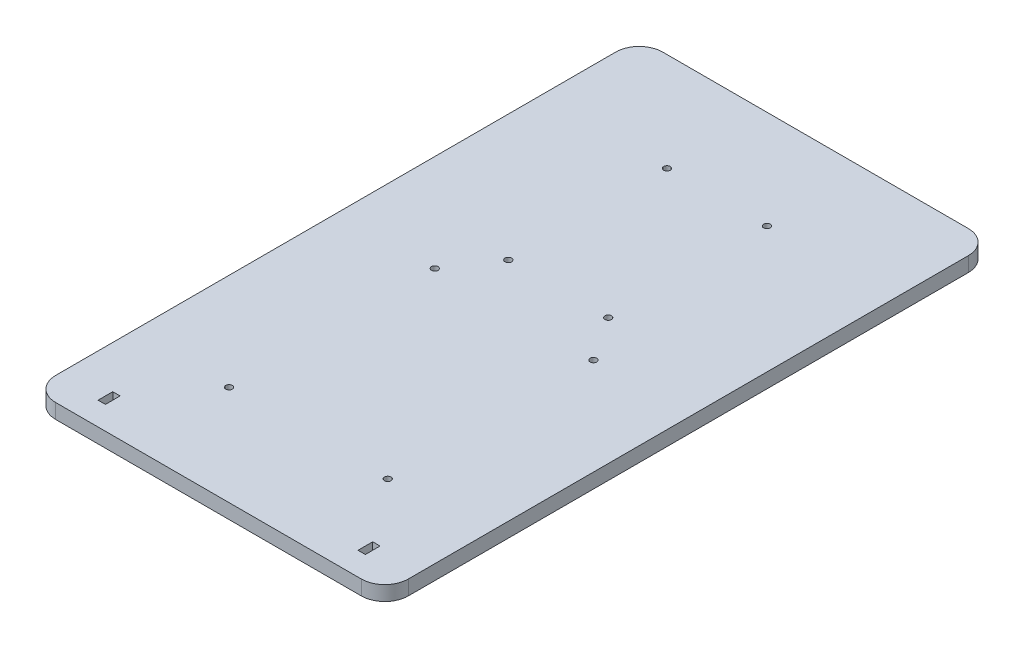
SolidWorks part; units mm, degrees
ref_plane "Front Plane" through (0, 0, 0) normal (0, 0, 1) x (1, 0, 0)
ref_plane "Top Plane" through (0, 0, 0) normal (0, 1, 0) x (1, 0, 0)
ref_plane "Right Plane" through (0, 0, 0) normal (1, 0, 0) x (0, 0, -1)
sketch "Sketch3" plane through (0, 0, 0) normal (0, 1, 0) x (1, 0, 0)
  line L4 (152.4, 0) -> (0, 0)
  line L5 (76.2, 262.3393) -> (76.2, 0) construction
  line L6 (18.4411, 16.3877) -> (21.6161, 16.3877)
  line L7 (18.4411, 16.3877) -> (18.4411, 10.0377)
  line L8 (18.4411, 10.0377) -> (21.6161, 10.0377)
  line L9 (21.6161, 16.3877) -> (21.6161, 10.0377)
  line L10 (133.9589, 10.0377) -> (130.7839, 10.0377)
  line L11 (130.7839, 16.3877) -> (130.7839, 10.0377)
  line L12 (133.9589, 16.3877) -> (130.7839, 16.3877)
  line L13 (133.9589, 16.3877) -> (133.9589, 10.0377)
  line L14 (0, 0) -> (0, 262.3393)
  line L15 (0, 262.3393) -> (152.4, 262.3393)
  line L16 (152.4, 262.3393) -> (152.4, 0)
  circle A6 centre (41.91, 43.18) radius 1.4224
  circle A7 centre (41.91, 132.08) radius 1.4224
  circle A8 centre (110.49, 132.08) radius 1.4224
  circle A9 centre (110.49, 43.18) radius 1.4224
  circle A10 centre (54.61, 151.1577) radius 1.4224
  circle A11 centre (54.61, 219.7377) radius 1.4224
  circle A12 centre (97.79, 151.1577) radius 1.4224
  circle A13 centre (97.79, 219.7377) radius 1.4224
  point P4 (0, 1.7138)
  point P5 (152.4, 1.9825)
  dimension "D10" = 43.18
  dimension "D13" = 68.58
  dimension "D5" = 152.4
  dimension "D6" = 3.175
  dimension "D7" = 6.35
  dimension "D11" = 88.9
  dimension "D12" = 68.58
  dimension "D14" = 43.18
extrude "Boss-Extrude1" add sketch "Sketch3" along normal blind 6.35
fillet "Fillet1" radius 10.16 4 edges at (0, 3.175, 0) (0, 3.175, -262.3393) (152.4, 3.175, 0) (152.4, 3.175, -262.3393)
